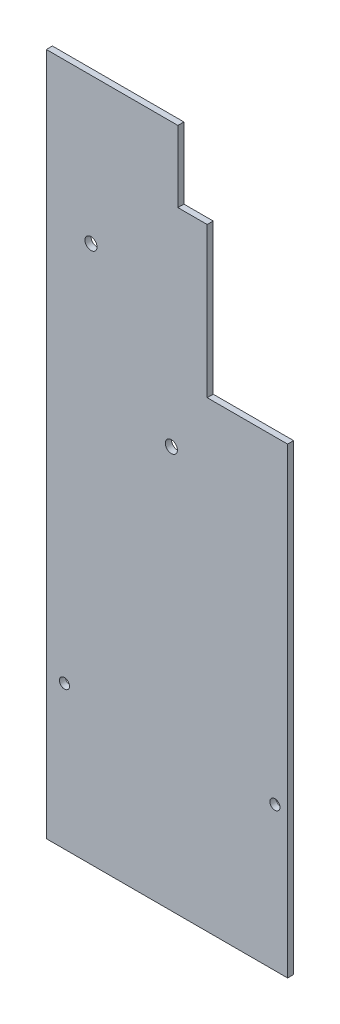
SolidWorks part; units mm, degrees
ref_plane "Plano frontal" through (0, 0, 0) normal (0, 0, 1) x (1, 0, 0)
ref_plane "Plano superior" through (0, 0, 0) normal (0, 1, 0) x (1, 0, 0)
ref_plane "Plano direito" through (0, 0, 0) normal (1, 0, 0) x (0, 0, -1)
sketch "Esboço2" plane through (0, 0, 25.4016) normal (0, 0, -1) x (-1, 0, 0)
  line L1 (40, 9.4624) -> (0, 9.4624)
  line L2 (-20, -160.5376) -> (40, -160.5376)
  line L3 (-20, -160.5376) -> (-20, -45.5376)
  line L4 (0, 9.4624) -> (0, -45.5376)
  line L5 (40, -160.5376) -> (40, 9.4624)
  line L7 (0, -45.5376) -> (-20, -45.5376)
  dimension "D1" = 60
  dimension "D2" = 40
  dimension "D3" = 55
  dimension "D4" = 115
extrude "Ressalto-extrusão1" add sketch "Esboço2" along normal blind 1.5
sketch "Esboço5" plane through (0, 0, 23.9016) normal (0, 0, -1) x (-1, 0, 0)
  line L1 (40, 9.4624) -> (0, 9.4624) construction
  line L3 (40, -160.5376) -> (40, 9.4624) construction
  circle A0 centre (28.9, -26.7876) radius 1.5
  dimension "D3" = 3
  dimension "D1" = 36.25
  dimension "D2" = 11.1
extrude "Corte-extrusão2" cut sketch "Esboço5" against normal up to next
hole_wizard "Broca de rosquear para tarraxa de M3x0.52" positions "Esboço14" profile "Esboço13" hole size "M3x0.5" standard "Métrico Ansi" end condition up to next
sketch "Esboço14" plane through (0, 0, 23.9016) normal (0, 0, -1) x (-1, 0, 0)
  point P0 (-16.8492, -124.7347)
  point P1 (35.5, -124.8089)
sketch "Esboço13" plane through (16.8492, -124.7347, 23.9016) normal (1, 0, 0) x (0, 1, 0)
  line L0 (0, 0) -> (0, 1.5)
  line L1 (0, 1.5) -> (1.25, 1.5)
  line L2 (1.25, 1.5) -> (1.25, 0)
  line L5 (1.25, 0) -> (0, 0)
  line L11 (0, -6.35) -> (0, 107.95) construction
  dimension "Thru Hole Dia." = 2.5
  dimension "Thru Hole Depth" = 1.5
sketch "Esboço15" plane through (0, 0, 23.9016) normal (0, 0, -1) x (-1, 0, 0)
  line L0 (40, 9.4624) -> (0, 9.4624) construction
  line L1 (0, 9.4624) -> (0, -45.5376) construction
  circle A0 centre (8.9, -60.5376) radius 1.5
  dimension "D1" = 3
  dimension "D2" = 70
  dimension "D3" = 8.9
extrude "Corte-extrusão3" cut sketch "Esboço15" against normal up to next
sketch "Esboço16" plane through (0, 0, 23.9016) normal (0, 0, -1) x (-1, 0, 0)
  line L0 (0, -8.2351) -> (7.2898, -8.2351)
  line L1 (0, 9.4624) -> (0, -45.5376) construction
  line L2 (7.2898, -8.2351) -> (7.2898, 9.4624)
  line L3 (40, 9.4624) -> (0, 9.4624) construction
  line L4 (7.2898, 9.4624) -> (0, 9.4624)
  line L5 (0, 9.4624) -> (0, -8.2351)
extrude "Corte-extrusão4" cut sketch "Esboço16" against normal up to next
equation "\"D2@Esboço15\" = \"Barramento_gy@Inversor3.SLDASM\"-60"
equation "\"D1@Esboço5\" = \"Barramento_sy@Inversor3.SLDASM\"-67.75"
equation "\"D2@Esboço5\"=\"Barramento_sx@Inversor3.SLDASM\"-32.4"
